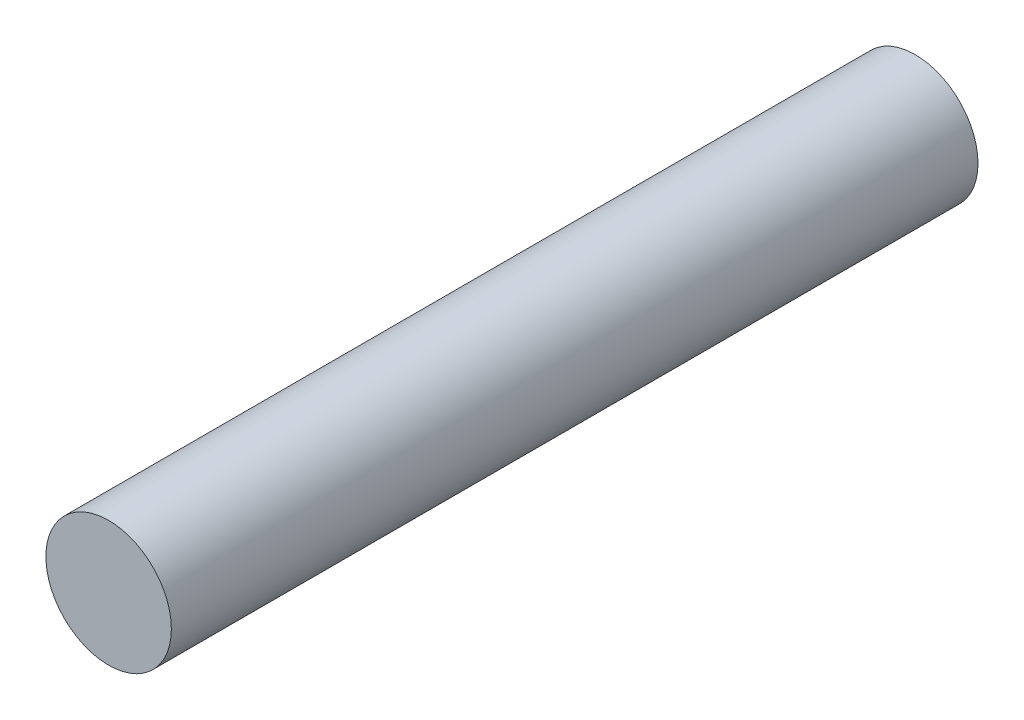
SolidWorks part; units mm, degrees
ref_plane "Front Plane" through (0, 0, 0) normal (0, 0, 1) x (1, 0, 0)
ref_plane "Top Plane" through (0, 0, 0) normal (0, 1, 0) x (1, 0, 0)
ref_plane "Right Plane" through (0, 0, 0) normal (1, 0, 0) x (0, 0, -1)
sketch "Sketch1" plane through (0, 0, 0) normal (0, 0, 1) x (1, 0, 0)
  circle A0 centre (0, 0) radius 1.778
  dimension "D1" = 3.556
extrude "Boss-Extrude1" add sketch "Sketch1" along normal mid plane 22.86
